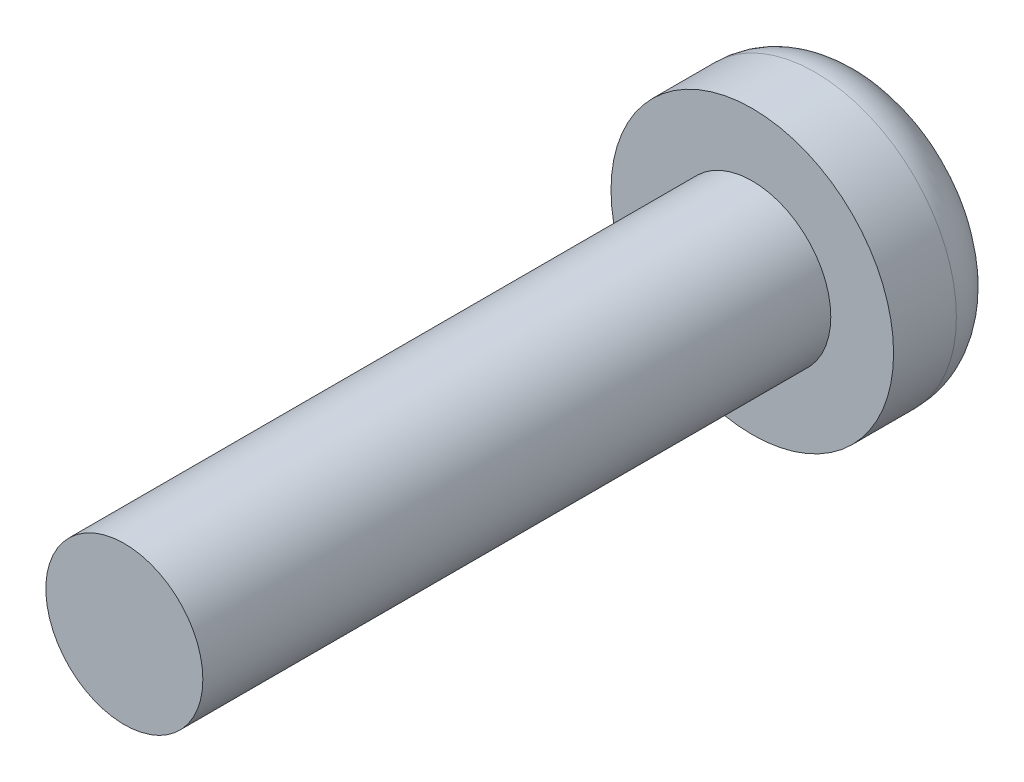
SolidWorks part; units mm, degrees
ref_plane "前视基准面" through (0, 0, 0) normal (0, 0, 1) x (1, 0, 0)
ref_plane "上视基准面" through (0, 0, 0) normal (0, 1, 0) x (1, 0, 0)
ref_plane "右视基准面" through (0, 0, 0) normal (1, 0, 0) x (0, 0, -1)
sketch "草图1" plane through (0, 0, 0) normal (0, 0, 1) x (1, 0, 0)
  circle A0 centre (0, 0) radius 1.5
extrude "凸台-拉伸1" add sketch "草图1" along normal blind 12
sketch "草图2" plane through (0, 0, 0) normal (0, 0, -1) x (-1, 0, 0)
  circle A0 centre (0, 0) radius 2.7
extrude "凸台-拉伸2" add sketch "草图2" along normal blind 2.2
fillet "圆角1" radius 1 1 edges at (-2.7, 0, -2.2)
